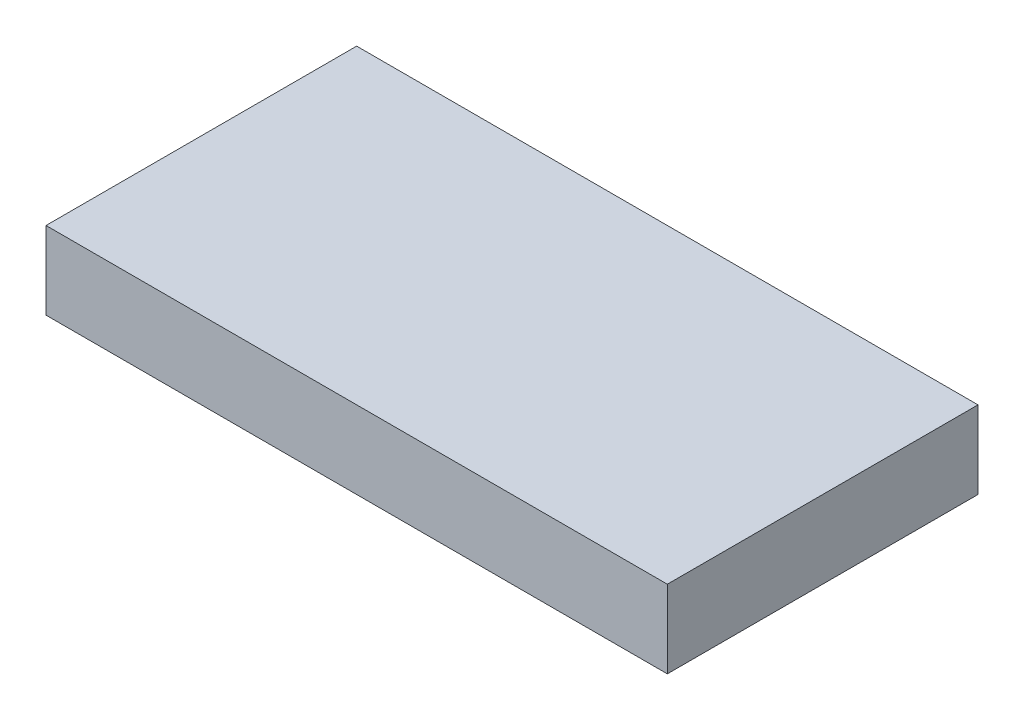
SolidWorks part; units mm, degrees
ref_plane "Front Plane" through (0, 0, 0) normal (0, 0, 1) x (1, 0, 0)
ref_plane "Top Plane" through (0, 0, 0) normal (0, 1, 0) x (1, 0, 0)
ref_plane "Right Plane" through (0, 0, 0) normal (1, 0, 0) x (0, 0, -1)
sketch "Sketch1" plane through (0, 0, 0) normal (0, 1, 0) x (1, 0, 0)
  line L1 (-29.2547, 7.3292) -> (10.7453, 7.3292)
  line L2 (-29.2547, 7.3292) -> (-29.2547, -12.6708)
  line L3 (-29.2547, -12.6708) -> (10.7453, -12.6708)
  line L4 (10.7453, 7.3292) -> (10.7453, -12.6708)
  dimension "D1" = 40
  dimension "D2" = 20
extrude "Boss-Extrude1" add sketch "Sketch1" along normal blind 5
